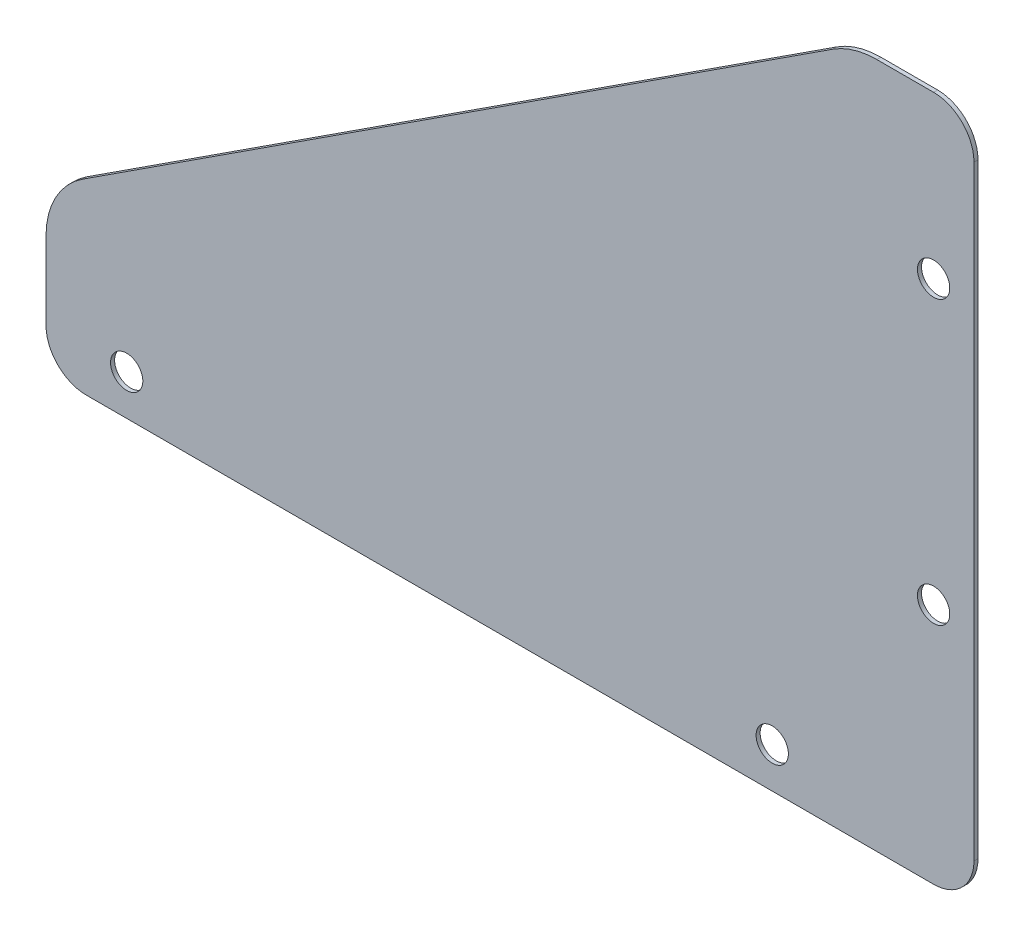
SolidWorks part; units mm, degrees
ref_plane "Front Plane" through (0, 0, 0) normal (0, 0, 1) x (1, 0, 0)
ref_plane "Top Plane" through (0, 0, 0) normal (0, 1, 0) x (1, 0, 0)
ref_plane "Right Plane" through (0, 0, 0) normal (1, 0, 0) x (0, 0, -1)
sketch "Sketch1" plane through (0, 0, 0) normal (0, 0, 1) x (1, 0, 0)
  line L0 (0, 5) -> (0, 80)
  line L1 (-5, 85) -> (-12.0356, 85)
  line L2 (-17.4855, 83.3844) -> (-110.4499, 22.9576)
  line L3 (-115, 14.5731) -> (-115, 5)
  line L4 (-110, 0) -> (-5, 0)
  arc A0 (-110.4499, 22.9576) -> (-115, 14.5731) centre (-105, 14.5731) ccw
  arc A1 (-12.0356, 85) -> (-17.4855, 83.3844) centre (-12.0356, 75) ccw
  arc A2 (-115, 5) -> (-110, 0) centre (-110, 5) ccw
  arc A3 (0, 5) -> (-5, 0) centre (-5, 5) cw
  arc A4 (0, 80) -> (-5, 85) centre (-5, 80) ccw
  circle A5 centre (-105, 5) radius 2
  circle A6 centre (-25, 5) radius 2
  circle A7 centre (-5, 30) radius 2
  circle A8 centre (-5, 65) radius 2
  point P8 (-115, 20)
  point P11 (-15, 85)
  point P14 (-115, 0)
  point P17 (0, 0)
  point P20 (0, 85)
  dimension "D5" = 10
  dimension "D6" = 5
  dimension "D7" = 4
  dimension "D10" = 4
  dimension "D1" = 85
  dimension "D2" = 20
  dimension "D3" = 15
  dimension "D4" = 115
  dimension "D8" = 10
  dimension "D11" = 5
  dimension "D12" = 30
  dimension "D9" = 2
  dimension "D13" = 2
extrude "Boss-Extrude1" add sketch "Sketch1" along normal blind 0.5
